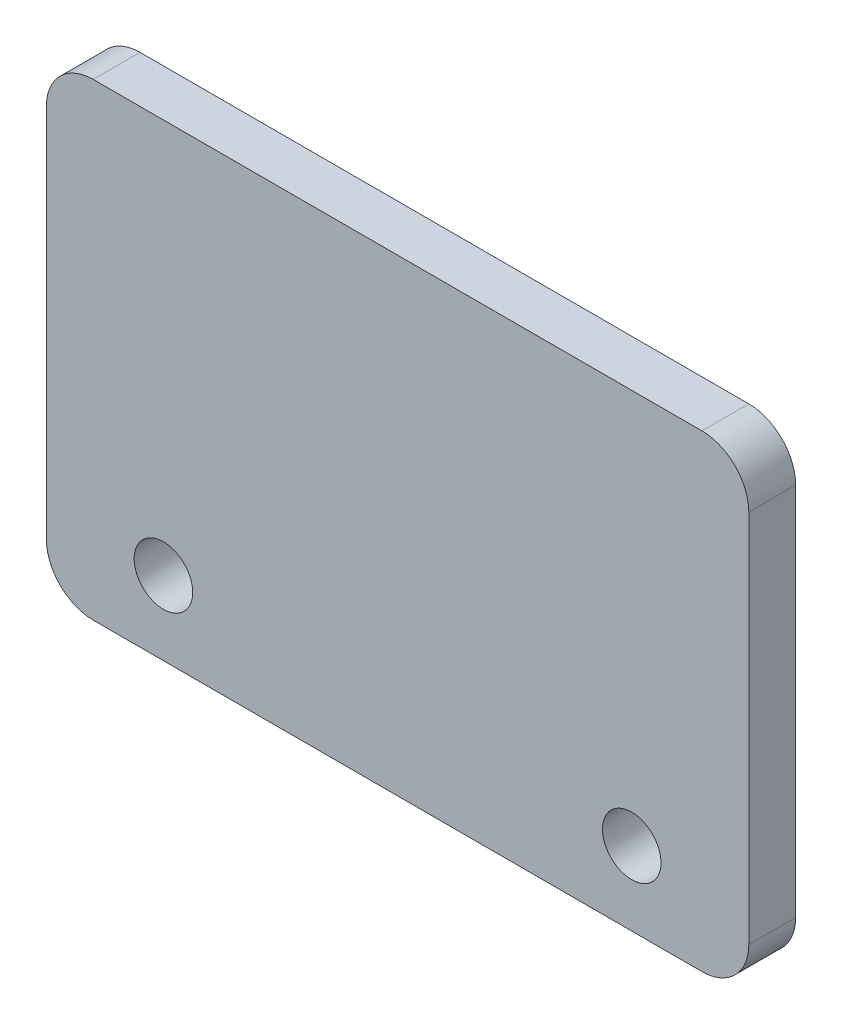
SolidWorks part; units mm, degrees
material "A-玻璃纤维"
ref_plane "前视基准面" through (0, 0, 0) normal (0, 0, 1) x (1, 0, 0)
ref_plane "上视基准面" through (0, 0, 0) normal (0, 1, 0) x (1, 0, 0)
ref_plane "右视基准面" through (0, 0, 0) normal (1, 0, 0) x (0, 0, -1)
other "Configuration Table"
sketch "草图1" plane through (0, 0, 0) normal (0, 0, 1) x (1, 0, 0)
  line L1 (-15, -10) -> (15, -10)
  line L2 (-15, -10) -> (-15, 10)
  line L3 (-15, 10) -> (15, 10)
  line L4 (15, -10) -> (15, 10)
  line L5 (-15, -10) -> (15, 10) construction
  line L6 (-15, 10) -> (15, -10) construction
  point P0 (0, 0)
  dimension "D1" = 30
  dimension "D2" = 20
extrude "凸台-拉伸1" add sketch "草图1" along normal blind 2
sketch "草图2" plane through (0, 0, 2) normal (0, 0, 1) x (1, 0, 0)
  circle A0 centre (-10, -6.85) radius 1.25 construction
  circle A1 centre (10, -6.85) radius 1.25 construction
  circle A2 centre (-10, -6.85) radius 1.25
  circle A3 centre (10, -6.85) radius 1.25
extrude "切除-拉伸1" cut sketch "草图2" against normal blind 2
fillet "圆角1" radius 2 4 edges at (-15, 10, 1) (15, 10, 1) (-15, -10, 1) (15, -10, 1)
